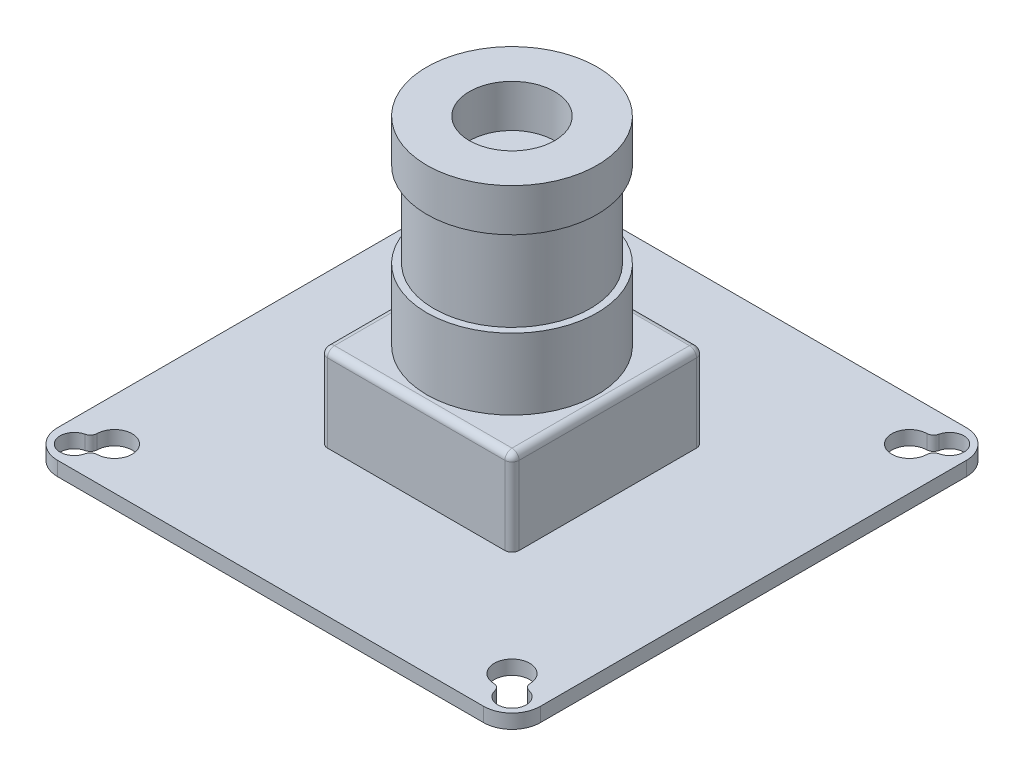
SolidWorks part; units mm, degrees
ref_plane "Front Plane" through (0, 0, 0) normal (0, 0, 1) x (1, 0, 0)
ref_plane "Top Plane" through (0, 0, 0) normal (0, 1, 0) x (1, 0, 0)
ref_plane "Right Plane" through (0, 0, 0) normal (1, 0, 0) x (0, 0, -1)
sketch "Sketch2" plane through (0, 0, 0) normal (0, 1, 0) x (1, 0, 0)
  line L1 (-17, -17) -> (17, -17)
  line L2 (-17, -17) -> (-17, 17)
  line L3 (-17, 17) -> (17, 17)
  line L4 (17, -17) -> (17, 17)
  line L5 (-17, -17) -> (17, 17) construction
  line L6 (-17, 17) -> (17, -17) construction
  point P0 (0, 0)
  dimension "D1" = 34
extrude "Boss-Extrude2" add sketch "Sketch2" along normal blind 1
fillet "Fillet1" radius 2 4 edges at (-17, 0.5, -17) (17, 0.5, -17) (-17, 0.5, 17) (17, 0.5, 17)
sketch "Sketch3" plane through (0, 1, 0) normal (0, 1, 0) x (1, 0, 0)
  line L1 (-6.75, -6.75) -> (6.75, -6.75)
  line L2 (-6.75, -6.75) -> (-6.75, 6.75)
  line L3 (-6.75, 6.75) -> (6.75, 6.75)
  line L4 (6.75, -6.75) -> (6.75, 6.75)
  line L5 (-6.75, -6.75) -> (6.75, 6.75) construction
  line L6 (-6.75, 6.75) -> (6.75, -6.75) construction
  point P0 (0, 0)
  dimension "D1" = 13.5
  dimension "D2" = 13.5
extrude "Boss-Extrude3" add sketch "Sketch3" along normal blind 6
sketch "Sketch4" plane through (0, 7, 0) normal (0, 1, 0) x (1, 0, 0)
  circle A0 centre (0, 0) radius 6
  dimension "D1" = 12
extrude "Boss-Extrude4" add sketch "Sketch4" along normal blind 5
fillet "Fillet2" radius 0.5 8 edges at (-6.75, 7, 0) (0, 7, -6.75) (6.75, 7, 0) (0, 7, 6.75) (-6.75, 4, -6.75) (-6.75, 4, 6.75) (6.75, 4, -6.75) (6.75, 4, 6.75)
sketch "Sketch5" plane through (0, 12, 0) normal (0, 1, 0) x (1, 0, 0)
  circle A0 centre (0, 0) radius 5.5
  circle A1 centre (0, 0) radius 6 construction
  dimension "D1" = 0.5
extrude "Boss-Extrude5" add sketch "Sketch5" along normal blind 6
sketch "Sketch6" plane through (0, 18, 0) normal (0, 1, 0) x (1, 0, 0)
  circle A0 centre (0, 0) radius 3
  circle A1 centre (0, 0) radius 6
  circle A2 centre (0, 0) radius 6 construction
  dimension "D1" = 6
extrude "Boss-Extrude6" add sketch "Sketch6" along normal blind 3
sketch "Sketch7" plane through (0, 1, 0) normal (0, 1, 0) x (1, 0, 0)
  line L0 (-14, 14) -> (-14, -14) construction
  line L1 (-14, -14) -> (14, -14) construction
  line L2 (14, -14) -> (14, 14) construction
  line L3 (14, 14) -> (-14, 14) construction
  line L4 (15, 17) -> (-15, 17) construction
  line L5 (17, -15) -> (17, 15) construction
  line L6 (14, 14) -> (15.4142, 15.4142) construction
  line L7 (-15.4142, 15.4142) -> (-14, 14) construction
  circle A0 centre (-14, 14) radius 1.25
  circle A1 centre (14, 14) radius 1.25
  circle A2 centre (14, -14) radius 1.25
  circle A3 centre (-14, -14) radius 1.25
  circle A4 centre (15.4142, 15.4142) radius 1
  circle A5 centre (15.4142, -15.4142) radius 1
  circle A6 centre (-15.4142, -15.4142) radius 1
  circle A7 centre (-15.4142, 15.4142) radius 1
  point P11 (0, 17)
  point P12 (0, 14)
  point P15 (17, 0)
  point P16 (14, 0)
  point P27 (0, 0)
  dimension "D3" = 2.5
  dimension "D6" = 2
  dimension "D1" = 28
  dimension "D2" = 28
  dimension "D4" = 135
  dimension "D5" = 2
  dimension "D7" = 4
extrude "Cut-Extrude1" cut sketch "Sketch7" against normal through all contours A6 A3 | A3 A6 | A3 A6 | A5 A2 | A2 A5 | A2 A5 | A4 A1 | A1 A4 | A1 A4 | A7 A0 | A0 A7 | A0 A7
fillet "Fillet3" radius 0.5 8 edges at (14.445, 0.5, -15.1681) (15.1681, 0.5, -14.445) (15.1681, 0.5, 14.445) (14.445, 0.5, 15.1681) (-15.1681, 0.5, 14.445) (-14.445, 0.5, 15.1681) (-15.1681, 0.5, -14.445) (-14.445, 0.5, -15.1681)
